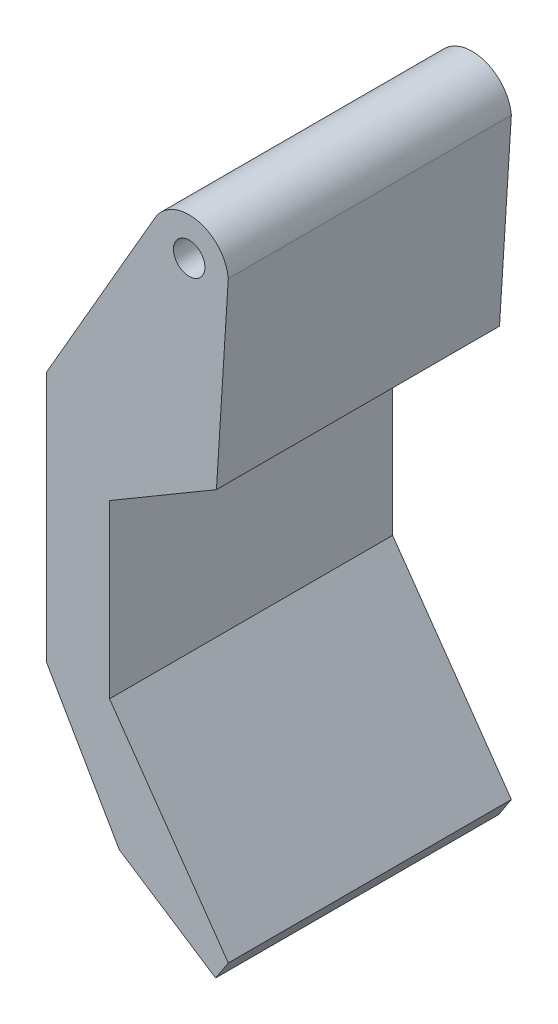
SolidWorks part; units mm, degrees
ref_plane "前视基准面" through (0, 0, 0) normal (0, 0, 1) x (1, 0, 0)
ref_plane "上视基准面" through (0, 0, 0) normal (0, 1, 0) x (1, 0, 0)
ref_plane "右视基准面" through (0, 0, 0) normal (1, 0, 0) x (0, 0, -1)
sketch "草图1" plane through (0, 0, 0) normal (0, 0, 1) x (1, 0, 0)
  line L0 (0.4413, 66.8945) -> (-16.8792, 36.8945)
  line L1 (-16.8792, 36.8945) -> (-16.8792, -3.1055)
  line L2 (-16.8792, -3.1055) -> (-5.3322, -23.1055)
  line L5 (-7.0008, 37.5151) -> (-6.8792, 37.579)
  line L26 (-5.3322, -23.1055) -> (9.9927, -33.1055)
  line L27 (11.9998, 64.1907) -> (10.1143, 34.1907)
  line L28 (10.1143, 34.1907) -> (-6.8792, 24.1907)
  line L29 (-6.8792, 24.1907) -> (-6.8792, 14.1907)
  line L32 (-6.8792, 14.1907) -> (-6.8792, -3.1055)
  line L35 (-6.8792, -3.1055) -> (11.9998, -30.0298)
  line L36 (11.9998, -30.0298) -> (9.9927, -33.1055)
  arc A4 (0.4413, 66.8945) -> (11.9998, 64.1907) centre (5.7669, 63.6033) cw
  dimension "D7" = 30
  dimension "D8" = 10
  dimension "D9" = 10
  dimension "D6" = 10
  dimension "D1" = 150
  dimension "D2" = 150
  dimension "D3" = 30
  dimension "D4" = 40
  dimension "D5" = 20
  dimension "D10" = 10
sketch "草图2" plane through (0, 0, 0) normal (0, 0, 1) x (1, 0, 0)
  circle A2 centre (5.7844, 63.8812) radius 2.5
  dimension "D1" = 5
extrude "凸台-拉伸4" add sketch "草图1" along normal blind 45
extrude "切除-拉伸1" cut sketch "草图2" along normal through all
